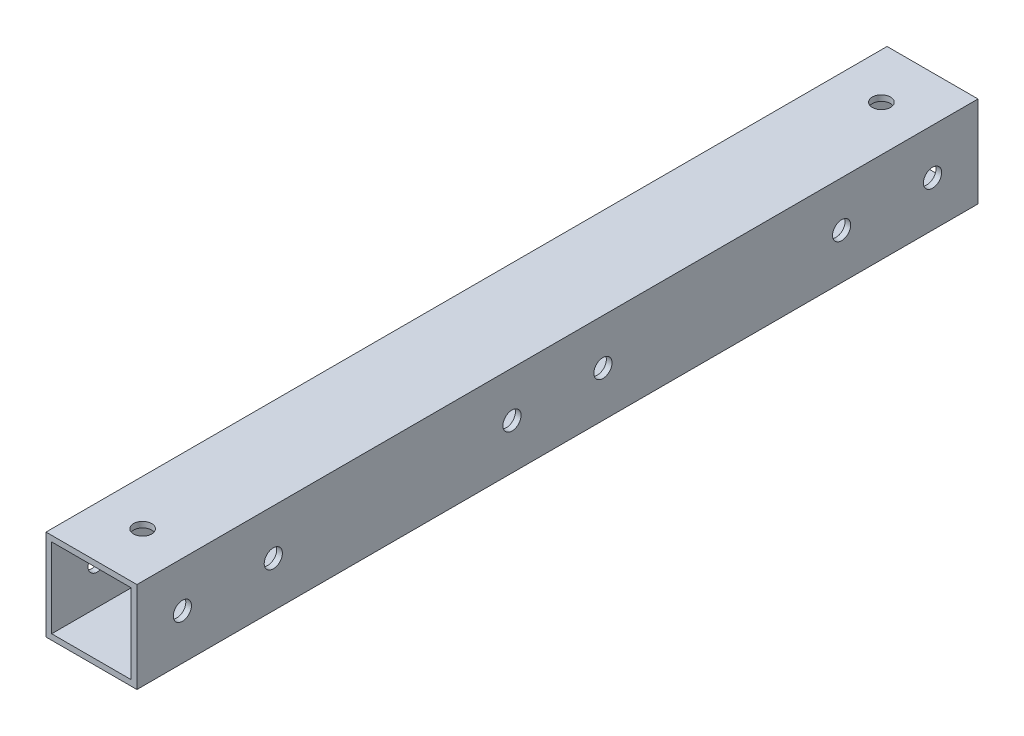
SolidWorks part; units mm, degrees
ref_plane "Front Plane" through (0, 0, 0) normal (0, 0, 1) x (1, 0, 0)
ref_plane "Top Plane" through (0, 0, 0) normal (0, 1, 0) x (1, 0, 0)
ref_plane "Right Plane" through (0, 0, 0) normal (1, 0, 0) x (0, 0, -1)
sketch "Sketch1" plane through (0, 0, 0) normal (0, 0, 1) x (1, 0, 0)
  line L1 (0, 0) -> (25.4, 0)
  line L2 (0, 0) -> (0, 25.4)
  line L3 (0, 25.4) -> (25.4, 25.4)
  line L4 (25.4, 0) -> (25.4, 25.4)
  line L5 (1.5875, 1.5875) -> (23.8125, 1.5875)
  line L6 (1.5875, 1.5875) -> (1.5875, 23.8125)
  line L7 (1.5875, 23.8125) -> (23.8125, 23.8125)
  line L8 (23.8125, 1.5875) -> (23.8125, 23.8125)
  dimension "D1" = 25.4
  dimension "D2" = 1.5875
  dimension "D3" = 1.5875
  dimension "D4" = 1.5875
  dimension "D5" = 1.5875
extrude "Boss-Extrude1" add sketch "Sketch1" along normal blind 234.95
sketch "Sketch4" plane through (25.4, 0, 0) normal (1, 0, 0) x (0, 0, -1)
  line L0 (-234.95, 25.4) -> (0, 25.4) construction
  line L1 (-234.95, 0) -> (-234.95, 25.4) construction
  line L2 (-117.475, 25.4) -> (-117.475, 0) construction
  line L3 (-234.95, 0) -> (0, 0) construction
  circle A0 centre (-222.25, 12.7) radius 2.54
  circle A2 centre (-196.85, 12.7) radius 2.54
  circle A12 centre (-38.1, 12.7) radius 2.54
  circle A13 centre (-12.7, 12.7) radius 2.54
  circle A14 centre (-104.775, 12.7) radius 2.54
  circle A15 centre (-130.175, 12.7) radius 2.54
  dimension "D1" = 5.08
  dimension "D2" = 12.7
  dimension "D3" = 12.7
  dimension "D4" = 2
  dimension "D5" = 12.7
extrude "Cut-Extrude3" cut sketch "Sketch4" against normal through all
sketch "Sketch5" plane through (0, 25.4, 0) normal (0, 1, 0) x (1, 0, 0)
  line L0 (0, -117.475) -> (25.4, -117.475) construction
  line L1 (0, -234.95) -> (0, 0) construction
  line L2 (25.4, -234.95) -> (25.4, 0) construction
  line L3 (12.7, -234.95) -> (12.7, 0) construction
  line L4 (25.4, -234.95) -> (0, -234.95) construction
  line L5 (25.4, 0) -> (0, 0) construction
  circle A0 centre (12.7, -220.6625) radius 2.54
  circle A1 centre (12.7, -14.2875) radius 2.54
  dimension "D1" = 5.08
  dimension "D2" = 14.2875
extrude "Cut-Extrude4" cut sketch "Sketch5" against normal up to next
